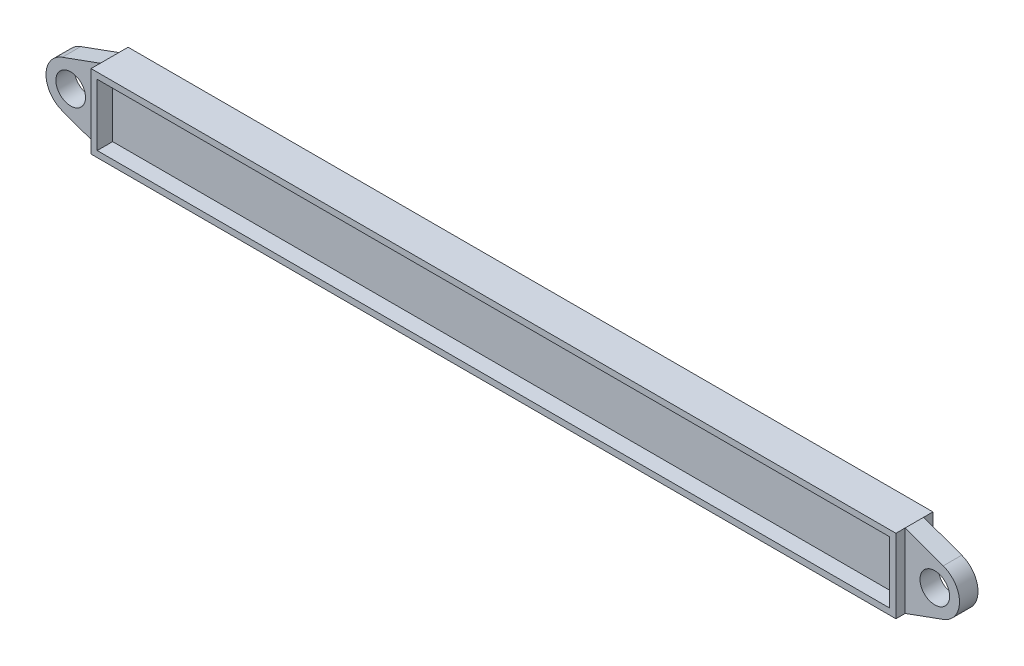
SolidWorks part; units mm, degrees
ref_plane "前视基准面" through (0, 0, 0) normal (0, 0, 1) x (1, 0, 0)
ref_plane "上视基准面" through (0, 0, 0) normal (0, 1, 0) x (1, 0, 0)
ref_plane "右视基准面" through (0, 0, 0) normal (1, 0, 0) x (0, 0, -1)
sketch "草图1" plane through (0, 0, 0) normal (0, 0, 1) x (1, 0, 0)
  line L4 (0, 20) -> (700, 20) construction
  line L6 (676, -10) -> (706.8303, 1.2025)
  line L7 (24, 50) -> (-6.8303, 38.7975)
  line L8 (350, 20) -> (350, -115.5667) construction
  line L9 (676, 50) -> (706.8303, 38.7975)
  line L10 (676, 50) -> (24, 50)
  line L11 (24, -10) -> (-6.8303, 1.2025)
  line L12 (676, -10) -> (24, -10)
  arc A0 (-6.8303, 38.7975) -> (-6.8303, 1.2025) centre (0, 20) ccw
  circle A1 centre (0, 20) radius 12
  arc A2 (706.8303, 38.7975) -> (706.8303, 1.2025) centre (700, 20) cw
  circle A3 centre (700, 20) radius 12
extrude "凸台-拉伸1" add sketch "草图1" along normal blind 30
sketch "草图2" plane through (0, 0, 30) normal (0, 0, 1) x (1, 0, 0)
  line L0 (24, 50) -> (-6.8303, 38.7975)
  line L1 (24, 50) -> (24, -10)
  line L2 (24, -10) -> (-6.8303, 1.2025)
  line L3 (706.8303, 38.7975) -> (676, 50)
  line L4 (676, 50) -> (676, -10)
  line L5 (676, -10) -> (706.8303, 1.2025)
  circle A0 centre (0, 20) radius 12
  arc A1 (-6.8303, 38.7975) -> (-6.8303, 1.2025) centre (0, 20) ccw
  arc A2 (706.8303, 1.2025) -> (706.8303, 38.7975) centre (700, 20) ccw
extrude "切除-拉伸1" cut sketch "草图2" against normal blind 7.5
sketch "草图3" plane through (0, 0, 0) normal (0, 0, -1) x (-1, 0, 0)
  line L0 (6.8303, 38.7975) -> (-24, 50)
  line L1 (-24, 50) -> (-24, -10)
  line L2 (-24, -10) -> (6.8303, 1.2025)
  line L3 (-706.8303, 38.7975) -> (-676, 50)
  line L4 (-676, 50) -> (-676, -10)
  line L5 (-676, -10) -> (-706.8303, 1.2025)
  arc A0 (6.8303, 1.2025) -> (6.8303, 38.7975) centre (0, 20) ccw
  arc A1 (-706.8303, 38.7975) -> (-706.8303, 1.2025) centre (-700, 20) ccw
extrude "切除-拉伸2" cut sketch "草图3" against normal blind 7.5
sketch "草图4" plane through (0, 0, 0) normal (0, 0, -1) x (-1, 0, 0)
  line L1 (-24, -10) -> (-676, -10) construction
  line L2 (-676, -10) -> (-676, 50) construction
  line L3 (-671, 45) -> (-671, -5)
  line L6 (-29, -5) -> (-29, 45)
  line L8 (-29, 45) -> (-671, 45)
  line L10 (-671, -5) -> (-29, -5)
  point P5 (0, 0)
  dimension "D1" = 642
  dimension "D2" = 50
  dimension "D3" = 5
  dimension "D4" = 5
extrude "切除-拉伸3" cut sketch "草图4" against normal blind 12.5
sketch "草图5" plane through (0, 0, 30) normal (0, 0, 1) x (1, 0, 0)
  line L0 (24, -10) -> (24, 50) construction
  line L1 (676, 50) -> (24, 50) construction
  line L3 (29, 45) -> (671, 45)
  line L4 (671, 45) -> (671, -5)
  line L5 (671, -5) -> (29, -5)
  line L6 (29, -5) -> (29, 45)
  dimension "D1" = 642
  dimension "D2" = 5
  dimension "D3" = 50
  dimension "D4" = 5
extrude "切除-拉伸4" cut sketch "草图5" against normal blind 12.5
